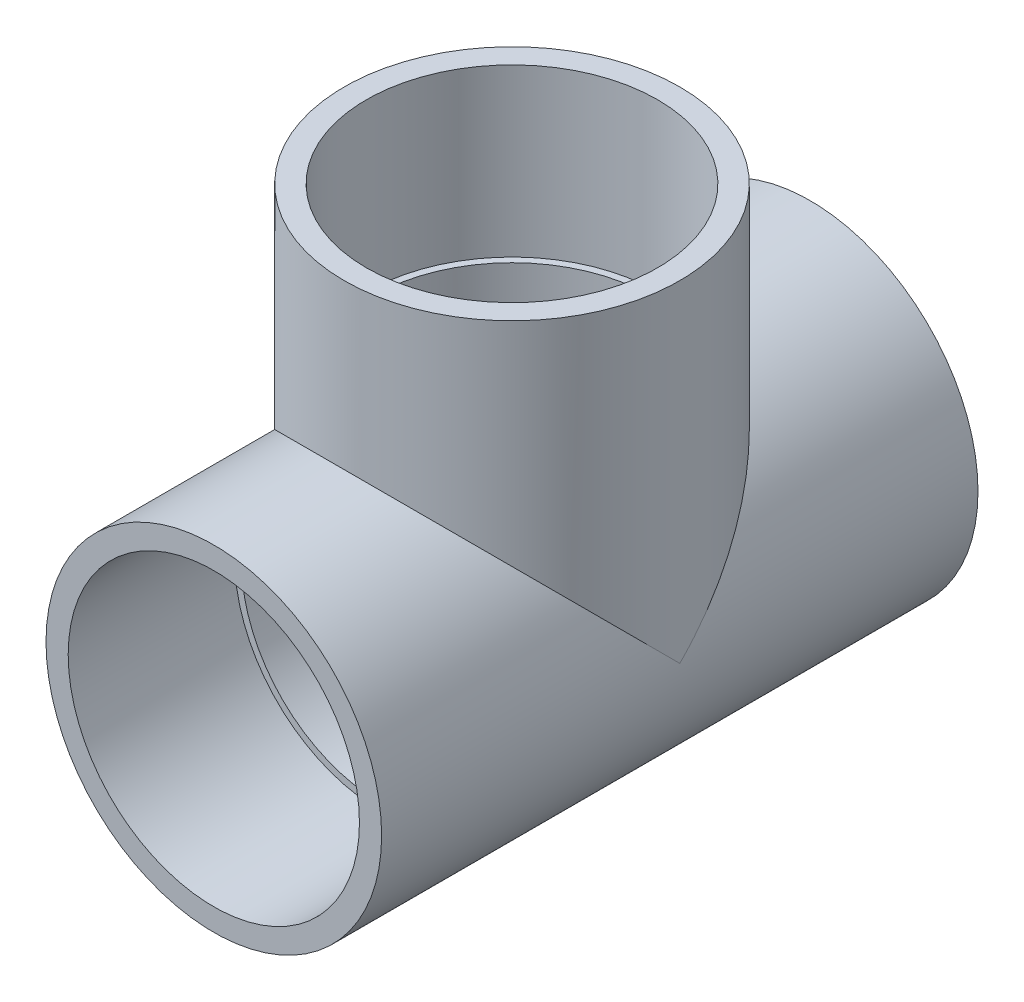
SolidWorks part; units mm, degrees
ref_plane "Front Plane" through (0, 0, 0) normal (0, 0, 1) x (1, 0, 0)
ref_plane "Top Plane" through (0, 0, 0) normal (0, 1, 0) x (1, 0, 0)
ref_plane "Right Plane" through (0, 0, 0) normal (1, 0, 0) x (0, 0, -1)
sketch "Sketch1" plane through (0, 0, 0) normal (0, 1, 0) x (1, 0, 0)
  line L0 (19.2087, 34.1313) -> (0, 34.1313)
  line L1 (0, 34.1313) -> (0, -34.1313)
  line L2 (0, -34.1313) -> (19.2087, -34.1313)
  line L3 (19.2087, -34.1313) -> (19.2087, 34.1313)
  line L4 (0, -118.244) -> (0, 82.7642) construction
  dimension "D1" = 68.2625
  dimension "D2" = 19.2087
revolve "Revolve1" add sketch "Sketch1" angle 360 about L4
sketch "Sketch2" plane through (0, 0, 0) normal (0, 0, 1) x (1, 0, 0)
  line L0 (0, 37.9413) -> (-19.2087, 37.9413)
  line L1 (-19.2087, 37.9413) -> (-19.2087, 0)
  line L2 (-19.2087, 0) -> (0, 0)
  line L3 (0, 0) -> (0, 37.9413)
  line L4 (0, 0) -> (0, 37.9413) construction
  line L5 (0, 0) -> (0, -19.2087) construction
  circle A0 centre (0, 0) radius 19.2087 construction
  dimension "D1" = 57.15
revolve "Revolve2" add sketch "Sketch2" angle 360 about L4
sketch "Sketch7" plane through (0, 0, 34.1313) normal (0, 0, 1) x (1, 0, 0)
  circle A0 centre (0, 0) radius 15.875
  dimension "D1" = 31.75
extrude "Cut-Extrude1" cut sketch "Sketch7" against normal through all
sketch "Sketch8" plane through (0, 37.9413, 0) normal (0, 1, 0) x (1, 0, 0)
  circle A0 centre (0, 0) radius 15.875
  dimension "D1" = 31.75
extrude "Cut-Extrude2" cut sketch "Sketch8" against normal up to next
sketch "Sketch9" plane through (0, 0, 34.1313) normal (0, 0, 1) x (1, 0, 0)
  circle A0 centre (0, 0) radius 16.6687
  dimension "D1" = 33.3375
extrude "Cut-Extrude3" cut sketch "Sketch9" against normal blind 19.05 contours A0
sketch "Sketch10" plane through (0, 0, -34.1313) normal (0, 0, -1) x (-1, 0, 0)
  circle A0 centre (0, 0) radius 16.6687
  dimension "D1" = 33.3375
extrude "Cut-Extrude4" cut sketch "Sketch10" against normal blind 19.05
sketch "Sketch11" plane through (0, 37.9413, 0) normal (0, 1, 0) x (1, 0, 0)
  circle A0 centre (0, 0) radius 16.6687
  dimension "D1" = 33.3375
extrude "Cut-Extrude5" cut sketch "Sketch11" against normal blind 19.05
